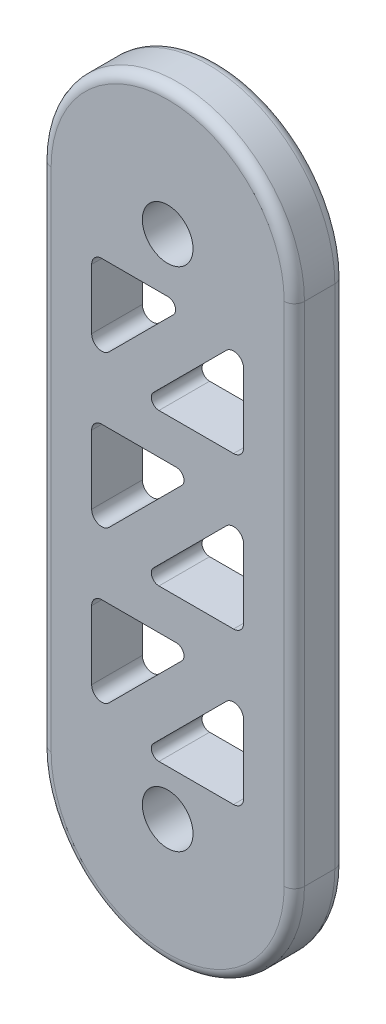
SolidWorks part; units mm, degrees
ref_plane "Front Plane" through (0, 0, 0) normal (0, 0, 1) x (1, 0, 0)
ref_plane "Top Plane" through (0, 0, 0) normal (0, 1, 0) x (1, 0, 0)
ref_plane "Right Plane" through (0, 0, 0) normal (1, 0, 0) x (0, 0, -1)
sketch "Sketch1" plane through (0, 0, 0) normal (0, 0, 1) x (1, 0, 0)
  line L0 (15, 0) -> (15, 100)
  line L2 (0, 0) -> (0, 100)
  line L4 (50, 0) -> (50, 100)
  line L5 (35, 0) -> (35, 100)
  arc A0 (50, 100) -> (0, 100) centre (25, 100) ccw
  arc A1 (0, 0) -> (50, 0) centre (25, 0) ccw
  circle A2 centre (25, 0) radius 5
  circle A3 centre (25, 100) radius 5
  arc A4 (35, 100) -> (15, 100) centre (25, 100) ccw
  arc A5 (15, 0) -> (35, 0) centre (25, 0) ccw
  dimension "D3" = 10
  dimension "D4" = 10
  dimension "D1" = 100
  dimension "D2" = 50
  dimension "D5" = 15
extrude "Boss-Extrude1" add sketch "Sketch1" along normal blind 10 contours L2 A1 L4 A0 A5 L0 A4 L5 | L0 A5 L5 A4 A2 A3
sketch "Sketch2" plane through (0, 0, 10) normal (0, 0, 1) x (1, 0, 0)
  line L0 (10, 100) -> (10, 0)
  line L1 (40, 0) -> (40, 100)
  line L2 (0, 100) -> (0, 0)
  line L3 (50, 0) -> (50, 100)
  line L4 (0, 100) -> (0, 0)
  line L5 (50, 0) -> (50, 100)
  line L6 (25, 99) -> (25, 100) construction
  line L7 (25.065, 89.3431) -> (10, 89.3431)
  line L16 (23.2782, 9) -> (40, 9)
  line L17 (40, 29.3431) -> (22.2175, 11.5607)
  line L18 (23.2782, 39) -> (40, 39)
  line L19 (27.8284, 47.1716) -> (22.2175, 41.5607)
  line L20 (27.8284, 47.1716) -> (40, 59.3431)
  line L21 (40, 69) -> (23.2782, 69)
  line L22 (22.2175, 71.5607) -> (40, 89.3431)
  line L25 (27.7825, 28.4393) -> (10, 10.6569)
  line L26 (10, 31) -> (26.7218, 31)
  line L27 (22.1716, 52.8284) -> (10, 40.6569)
  line L28 (22.1716, 52.8284) -> (27.7825, 58.4393)
  line L29 (26.7218, 61) -> (10, 61)
  line L30 (10, 70.6569) -> (26.1256, 86.7825)
  line L47 (25, 89.3431) -> (25, 91) construction
  arc A0 (10, 0) -> (40, 0) centre (25, 0) ccw
  arc A1 (40, 100) -> (10, 100) centre (25, 100) ccw
  arc A2 (0, 0) -> (50, 0) centre (25, 0) ccw
  arc A3 (50, 100) -> (0, 100) centre (25, 100) ccw
  arc A4 (0, 0) -> (50, 0) centre (25, 0) ccw
  arc A5 (50, 100) -> (0, 100) centre (25, 100) ccw
  arc A6 (26.1256, 86.7825) -> (25.065, 89.3431) centre (25.065, 87.8431) ccw
  arc A7 (22.2175, 71.5607) -> (23.2782, 69) centre (23.2782, 70.5) ccw
  arc A8 (26.7218, 61) -> (27.7825, 58.4393) centre (26.7218, 59.5) cw
  arc A9 (22.2175, 41.5607) -> (23.2782, 39) centre (23.2782, 40.5) ccw
  arc A10 (26.7218, 31) -> (27.7825, 28.4393) centre (26.7218, 29.5) cw
  arc A11 (22.2175, 11.5607) -> (23.2782, 9) centre (23.2782, 10.5) ccw
  dimension "D3" = 1.5
  dimension "D1" = 0
  dimension "D2" = 10
extrude "Cut-Extrude2" cut sketch "Sketch2" against normal blind 10 contours L30 A6 L7 L0 | L22 A7 L21 L1 | A8 L29 L0 L27 L28 | L19 A9 L18 L1 L20 | A10 L26 L0 L25 | L17 A11 L16 L1
fillet "Fillet1" radius 2 12 edges at (40, 89.3431, 5) (40, 69, 5) (10, 89.3431, 5) (10, 70.6569, 5) (10, 40.6569, 5) (10, 61, 5) (40, 59.3431, 5) (10, 31, 5) (10, 10.6569, 5) (40, 29.3431, 5) (40, 9, 5) (40, 39, 5)
fillet "Fillet2" radius 2 8 edges at (25, -25, 10) (50, 50, 10) (25, 125, 10) (25, -25, 0) (50, 50, 0) (25, 125, 0) (0, 50, 10) (0, 50, 0)
